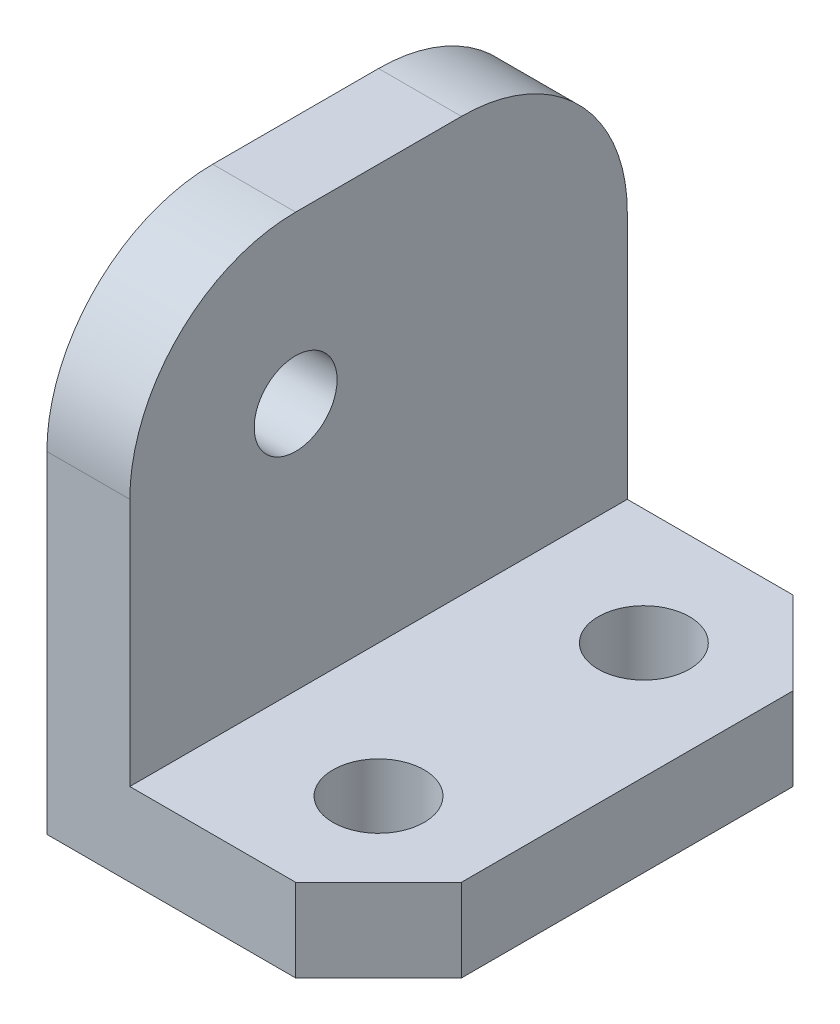
SolidWorks part; units mm, degrees
material "Alumina"
ref_plane "Front Plane" through (0, 0, 0) normal (0, 0, 1) x (1, 0, 0)
ref_plane "Top Plane" through (0, 0, 0) normal (0, 1, 0) x (1, 0, 0)
ref_plane "Right Plane" through (0, 0, 0) normal (1, 0, 0) x (0, 0, -1)
sketch "Sketch1" plane through (0, 0, 0) normal (0, 0, 1) x (1, 0, 0)
  line L0 (0, 0) -> (0, 38)
  line L1 (0, 38) -> (5, 38)
  line L2 (5, 38) -> (5, 5)
  line L3 (5, 5) -> (20, 5)
  line L4 (20, 5) -> (20, 0)
  line L5 (20, 0) -> (0, 0)
  dimension "D1" = 5
  dimension "D2" = 38
  dimension "D3" = 20
extrude "Boss-Extrude1" add sketch "Sketch1" along normal blind 30
sketch "Sketch2" plane through (5, 0, 0) normal (1, 0, 0) x (0, 0, -1)
  line L0 (-30, 20) -> (0, 20) construction
  line L3 (-30, 5) -> (-30, 38) construction
  line L4 (-30, 0) -> (0, 0) construction
  line L6 (0, 5) -> (0, 38) construction
  point P4 (-20, 20)
  dimension "D1" = 10
  dimension "D2" = 20
hole_wizard "M10 Tapped Hole1" [suppressed] positions "Sketch5" profile "Sketch6" tap size "M10" standard "ISO"
sketch "Sketch5" plane through (5, 0, 0) normal (1, 0, 0) x (0, 0, -1)
  point P0 (-20, 20)
sketch "Sketch6" plane through (5, 20, 20) normal (0, 1, 0) x (0, 0, -1)
  line L0 (0, 0) -> (0, 5)
  line L1 (0, 5) -> (4.25, 5)
  line L2 (4.25, 5) -> (4.25, 0)
  line L5 (4.25, 0) -> (0, 0)
  line L11 (0, -6.35) -> (0, 107.95) construction
  dimension "Thru Tap Drill Dia." = 8.5
  dimension "Thru Tap Drill Depth" = 5
cosmetic thread "Hole Thread1" [suppressed] parameters "D2"=10
hole_wizard "M6 Tapped Hole2" positions "Sketch11" profile "Sketch12" tap size "M6" standard "ISO" end condition through all
sketch "Sketch11" plane through (5, 0, 0) normal (1, 0, 0) x (0, 0, -1)
  point P0 (-20, 20)
sketch "Sketch12" plane through (5, 20, 20) normal (0, 1, 0) x (0, 0, -1)
  line L0 (0, 0) -> (0, 5)
  line L1 (0, 5) -> (2.5, 5)
  line L2 (2.5, 5) -> (2.5, 0)
  line L5 (2.5, 0) -> (0, 0)
  line L11 (0, -6.35) -> (0, 107.95) construction
  dimension "Thru Tap Drill Dia." = 5
  dimension "Thru Tap Drill Depth" = 5
cosmetic thread "Hole Thread3" parameters "D2"=6
sketch "Sketch8" plane through (0, 5, 0) normal (0, 1, 0) x (1, 0, 0)
  line L0 (20, -15) -> (13, -15) construction
  line L1 (20, -30) -> (20, 0) construction
  line L2 (13, -23) -> (13, -7) construction
  line L3 (20, -30) -> (5, -30) construction
  circle A0 centre (13, -7) radius 2.5
  circle A1 centre (13, -23) radius 2.5
  point P7 (13, -15)
  dimension "D2" = 5
  dimension "D1" = 7
  dimension "D3" = 7
hole_wizard "Ø5.5 (5.5) Diameter Hole1" positions "Sketch9" profile "Sketch10" hole size "Ø5.5" standard "ISO" end condition through all
sketch "Sketch9" plane through (0, 5, 0) normal (0, 1, 0) x (1, 0, 0)
  point P0 (13, -7)
  point P3 (13, -23)
sketch "Sketch10" plane through (13, 5, 7) normal (1, 0, 0) x (0, 0, 1)
  line L0 (0, 0) -> (0, 5)
  line L1 (0, 5) -> (2.75, 5)
  line L2 (2.75, 5) -> (2.75, 0)
  line L5 (2.75, 0) -> (0, 0)
  line L11 (0, -6.35) -> (0, 107.95) construction
  dimension "Thru Hole Dia." = 5.5
  dimension "Thru Hole Depth" = 5
mirror "Mirror2" [suppressed]
cosmetic thread "Hole Thread2" [suppressed] parameters "D2"=10
cosmetic thread "Hole Thread4" parameters "D2"=6
delete or keep bodies "Body-Delete/Keep 1" [suppressed] type delete bodies bodies 104
fillet "Fillet1" [suppressed] radius 10
fillet "Fillet2" [suppressed] radius 10
sketch "Sketch13" plane through (5, 0, 0) normal (1, 0, 0) x (0, 0, -1)
  line L0 (-30, 5) -> (-30, 38) construction
  line L1 (-20, 30) -> (0, 30)
  line L2 (0, 5) -> (0, 38) construction
  line L3 (-30, 38) -> (0, 38) construction
  line L4 (0, 30) -> (0, 38)
  line L5 (-30, 38) -> (0, 38)
  line L6 (-30, 20) -> (-30, 38)
  arc A0 (-20, 30) -> (-30, 20) centre (-20, 20) ccw
  point P9 (-20, 30)
extrude "Cut-Extrude1" cut sketch "Sketch13" against normal through all
fillet "Fillet3" radius 10 1 edges at (2.5, 30, 0)
chamfer "Chamfer1" distance 5 angle 45 2 edges at (20, 2.5, 0) (20, 2.5, 30)
